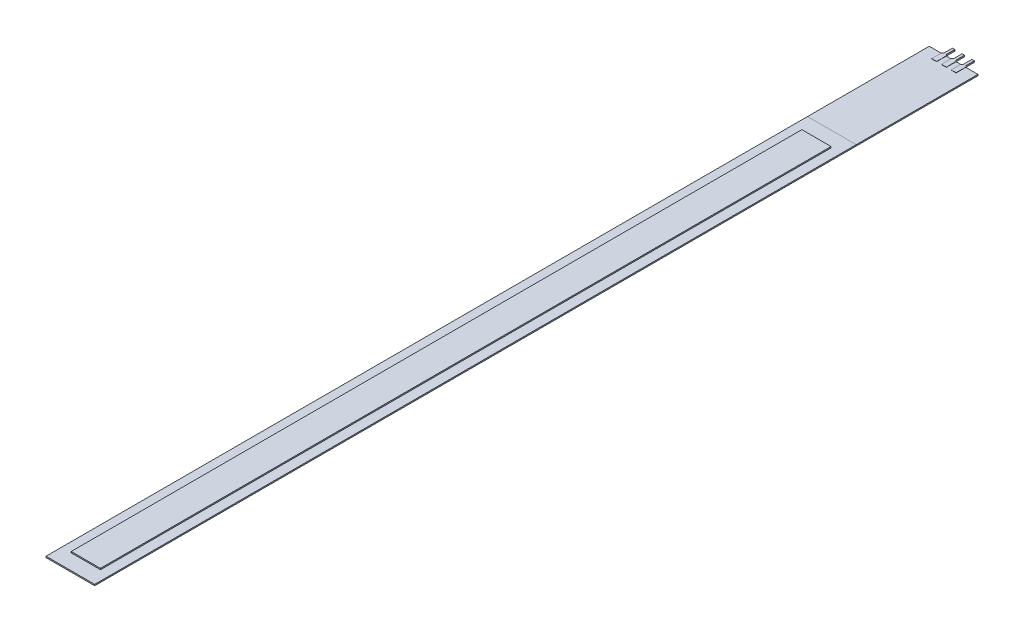
SolidWorks part; units mm, degrees
ref_plane "Front Plane" through (0, 0, 0) normal (0, 0, 1) x (1, 0, 0)
ref_plane "Top Plane" through (0, 0, 0) normal (0, 1, 0) x (1, 0, 0)
ref_plane "Right Plane" through (0, 0, 0) normal (1, 0, 0) x (0, 0, -1)
sketch "Sketch1" plane through (0, 0, 0) normal (0, 1, 0) x (1, 0, 0)
  line L6 (-5, 78.175) -> (5, 78.175)
  line L10 (-5, 78.175) -> (-5, -78.175)
  line L11 (-5, -78.175) -> (5, -78.175)
  line L12 (5, 78.175) -> (5, -78.175)
  line L13 (-5, 78.175) -> (5, -78.175) construction
  line L14 (-5, -78.175) -> (5, 78.175) construction
  point P0 (0, 0)
  dimension "D1" = 10
  dimension "D2" = 156.35
extrude "Boss-Extrude1" add sketch "Sketch1" along normal blind 0.255
sketch "Sketch2" plane through (0, 0.255, 0) normal (0, 1, 0) x (1, 0, 0)
  line L0 (0, 78.175) -> (0, -78.175) construction
  line L4 (-3, 75.005) -> (3, 75.005)
  line L5 (-3, 75.005) -> (-3, -74.995)
  line L6 (-3, -74.995) -> (3, -74.995)
  line L7 (3, 75.005) -> (3, -74.995)
  line L9 (5, 78.175) -> (-5, 78.175) construction
  line L10 (-5, -78.175) -> (5, -78.175) construction
  line L11 (5, -78.175) -> (5, 78.175) construction
  dimension "D1" = 6
  dimension "D2" = 150
  dimension "D3" = 3.17
  dimension "D4" = 2
extrude "Boss-Extrude2" add sketch "Sketch2" along normal blind 0.255
sketch "Sketch3" plane through (0, 0, 0) normal (0, 1, 0) x (1, 0, 0)
  line L0 (5, -78.175) -> (5, 78.175) construction
  line L1 (-5, 78.175) -> (5, 78.175)
  line L2 (-5, 78.175) -> (-5, 103.175)
  line L3 (-5, 103.175) -> (5, 103.175)
  line L4 (5, 78.175) -> (5, 103.175)
  dimension "D1" = 25
extrude "Boss-Extrude4" add sketch "Sketch3" along normal up to surface (0.255 mm away) separate body up to face at (0, 0.255, -0.005)
sketch "Sketch6" plane through (0, 0, 0) normal (0, 1, 0) x (1, 0, 0)
  line L0 (0, 0) -> (0, 102.0209) construction
  line L1 (5, 103.175) -> (-5, 103.175) construction
  line L2 (-0.5, 101.175) -> (0.5, 101.175)
  line L3 (-0.5, 101.175) -> (-0.5, 103.175)
  line L4 (-0.5, 103.175) -> (0.5, 103.175) construction
  line L5 (0.5, 101.175) -> (0.5, 103.175)
  line L6 (-0.5, 103.175) -> (-0.25, 103.425)
  line L7 (0.5, 103.175) -> (0.25, 103.425)
  line L8 (-0.25, 103.425) -> (-0.25, 105.175)
  line L9 (-0.25, 105.175) -> (0.25, 105.175)
  line L10 (0.25, 105.175) -> (0.25, 103.425)
  line L11 (2.25, 105.175) -> (2.25, 103.425)
  line L12 (2.5, 103.175) -> (2.25, 103.425)
  line L13 (2.5, 101.175) -> (2.5, 103.175)
  line L14 (1.5, 101.175) -> (2.5, 101.175)
  line L15 (1.5, 101.175) -> (1.5, 103.175)
  line L16 (1.5, 103.175) -> (1.75, 103.425)
  line L17 (1.75, 103.425) -> (1.75, 105.175)
  line L18 (1.75, 105.175) -> (2.25, 105.175)
  line L19 (0.25, 105.175) -> (2.25, 105.175) construction
  line L20 (-1.75, 105.175) -> (-2.25, 105.175)
  line L21 (-1.75, 103.425) -> (-1.75, 105.175)
  line L22 (-1.5, 103.175) -> (-1.75, 103.425)
  line L23 (-1.5, 101.175) -> (-1.5, 103.175)
  line L24 (-1.5, 101.175) -> (-2.5, 101.175)
  line L25 (-2.5, 101.175) -> (-2.5, 103.175)
  line L26 (-2.5, 103.175) -> (-2.25, 103.425)
  line L27 (-2.25, 105.175) -> (-2.25, 103.425)
  dimension "D1" = 1
  dimension "D2" = 2
  dimension "D3" = 45
  dimension "D4" = 0.5
  dimension "D5" = 2
  dimension "D7" = 2
  dimension "D6" = 2
extrude "Boss-Extrude5" add sketch "Sketch6" along normal blind 0.3
